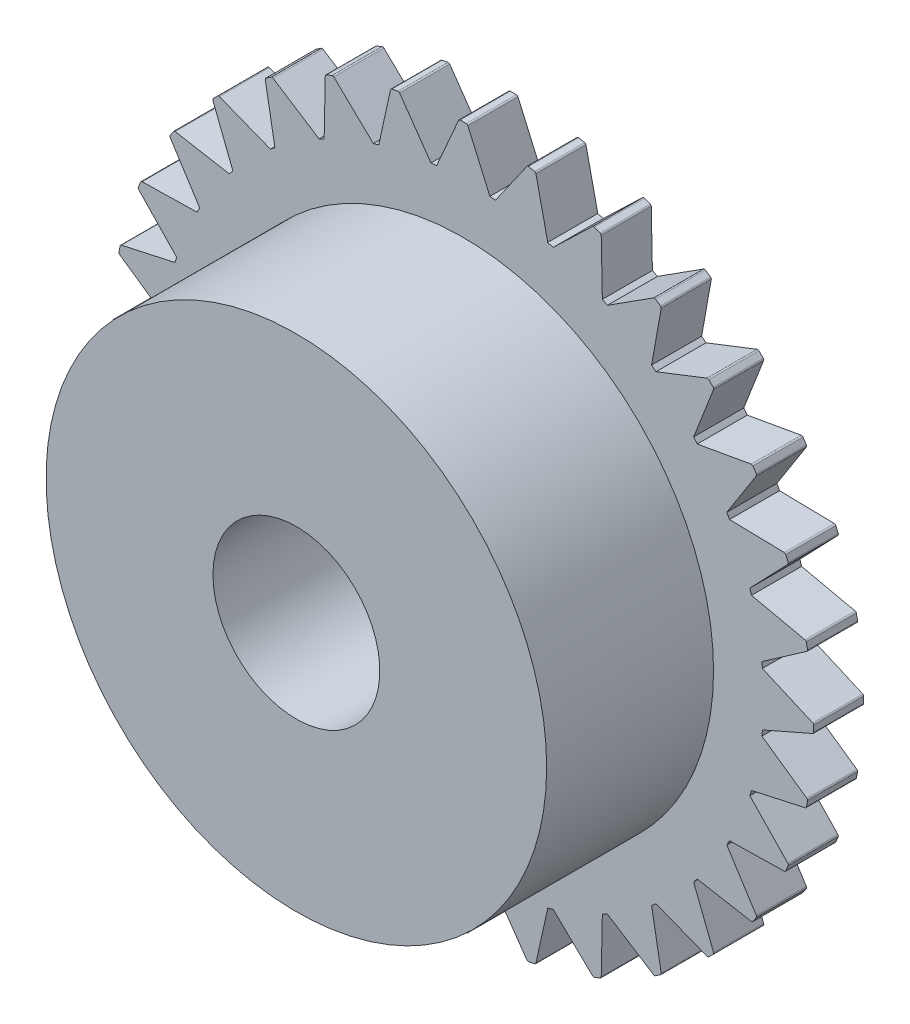
SolidWorks part; units mm, degrees
ref_plane "Front Plane" through (0, 0, 0) normal (0, 0, 1) x (1, 0, 0)
ref_plane "Top Plane" through (0, 0, 0) normal (0, 1, 0) x (1, 0, 0)
ref_plane "Right Plane" through (0, 0, 0) normal (1, 0, 0) x (0, 0, -1)
sketch "Sketch1" plane through (0, 0, 0) normal (0, 0, 1) x (1, 0, 0)
  line L0 (0, 0) -> (0, 18) construction
  circle A0 centre (0, 0) radius 18
  dimension "D1" = 36
extrude "Boss-Extrude1" add sketch "Sketch1" along normal blind 3
sketch "Sketch2" plane through (0, 0, 3) normal (0, 0, 1) x (1, 0, 0)
  line L0 (0, 0) -> (0, 18) construction
  line L1 (-0.2762, 20.9401) -> (-1.75, 17.5761)
  line L2 (-1.75, 17.5761) -> (1.75, 17.5761)
  line L3 (1.75, 17.5761) -> (0.2762, 20.9401)
  line L4 (-0.1846, 21) -> (0.1846, 21)
  circle A0 centre (0, 0) radius 18 construction
  arc A1 (0.1846, 21) -> (0.2762, 20.9401) centre (0.1846, 20.9) cw
  arc A2 (-0.1846, 21) -> (-0.2762, 20.9401) centre (-0.1846, 20.9) ccw
  point P2 (0, 0)
  point P6 (0, 0)
  point P10 (0, 17.5761)
  point P14 (2.25, 17.8261)
  point P17 (0.25, 21)
  point P20 (-0.25, 21)
  dimension "D5" = 0.1
  dimension "D1" = 21
  dimension "D2" = 3.4239
  dimension "D3" = 3.5
  dimension "D4" = 0.5
extrude "Boss-Extrude2" add sketch "Sketch2" against normal blind 3
sketch "Sketch3" plane through (0, 0, 3) normal (0, 0, 1) x (1, 0, 0)
  circle A0 centre (0, 0) radius 15
  dimension "D1" = 30
extrude "Boss-Extrude3" add sketch "Sketch3" along normal blind 10
sketch "Sketch4" plane through (0, 0, 0) normal (0, 0, -1) x (-1, 0, 0)
  circle A0 centre (0, 0) radius 5
  dimension "D1" = 10
extrude "Cut-Extrude1" cut sketch "Sketch4" against normal through all both and the other way through all contours A0
pattern_circular "CirPattern2" count 32 over 360 about axis through (0, 0, 0) along (0, 0, 1) of "Boss-Extrude2"
